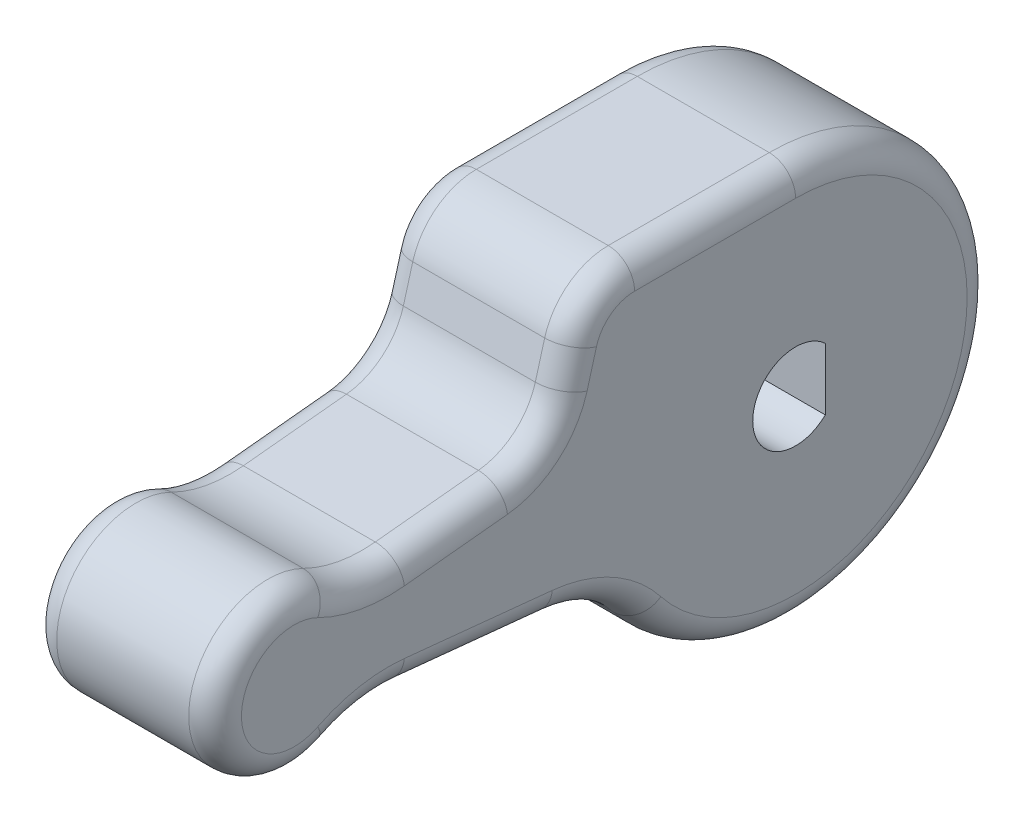
SolidWorks part; units mm, degrees
material "ABS"
ref_plane "Front Plane" through (0, 0, 0) normal (0, 0, 1) x (1, 0, 0)
ref_plane "Top Plane" through (0, 0, 0) normal (0, 1, 0) x (1, 0, 0)
ref_plane "Right Plane" through (0, 0, 0) normal (1, 0, 0) x (0, 0, -1)
sketch "Sketch1" plane through (0, 0, 0) normal (1, 0, 0) x (0, 0, -1)
  line L0 (1.125, -1.1726) -> (1.125, 1.1726)
  line L1 (-22, 0) -> (-19, 0) construction
  line L2 (-19, 0) -> (0, 0) construction
  line L3 (-16.7639, 2) -> (-6.8739, 3)
  line L4 (-16.7639, -2) -> (-6.8739, -3)
  line L5 (0, 0) -> (7.5, 0) construction
  line L6 (-1.625, 0) -> (1.125, 0) construction
  arc A0 (1.125, 1.1726) -> (1.125, -1.1726) centre (0, 0) ccw
  arc A1 (-6.8739, -3) -> (-6.8739, 3) centre (0, 0) ccw
  arc A2 (-16.7639, 2) -> (-16.7639, -2) centre (-19, 0) ccw
  dimension "D1" = 6
  dimension "D2" = 15
  dimension "D4" = 6
  dimension "D6" = 1.625
  dimension "D3" = 22
  dimension "D5" = 4
  dimension "D7" = 2.75
extrude "Boss-Extrude1" add sketch "Sketch1" along normal mid plane 7
fillet "Fillet1" radius 5 4 edges at (0, 2, 16.7639) (0, -3, 6.8739) (0, -2, 16.7639) (0, 3, 6.8739)
ref_plane "Plane1" through (0, 0, -7.625) normal (0, 0, 1) x (1, 0, 0)
hole_wizard "Hole1" positions "Sketch2" profile "Sketch3" legacy
sketch "Sketch2" plane through (0, 0, -7.625) normal (0, 0, 1) x (1, 0, 0)
  point P0 (0, 0)
sketch "Sketch3" plane through (0, 0, -7.625) normal (1, 0, 0) x (0, 1, 0)
  line L0 (0, 0) -> (0, 8)
  line L1 (0, 8) -> (1.25, 8)
  line L2 (1.25, 8) -> (1.25, 3)
  line L3 (1.25, 3) -> (1.75, 3)
  line L4 (1.75, 3) -> (1.75, 0)
  line L5 (1.75, 0) -> (0, 0)
  line L6 (0, 110) -> (0, -10) construction
  dimension "Diameter" = 2.5
  dimension "Depth" = 8
  dimension "C-Bore Diameter" = 3.5
  dimension "C-Bore Depth" = 3
sketch "Sketch4" plane through (3.5, 0, 0) normal (1, 0, 0) x (0, 0, -1)
  line L0 (0, 7.5) -> (-8, 7.5)
  line L1 (-8, 7.5) -> (-9.3226, 2.7524)
  arc A0 (-5.8954, -4.6362) -> (-5.8954, 4.6362) centre (0, 0) ccw construction
  arc A1 (-9.3226, 2.7524) -> (-5.8954, 4.6362) centre (-9.8256, 7.727) ccw construction
  arc A2 (-9.3226, 2.7524) -> (-5.8954, 4.6362) centre (-9.8256, 7.727) ccw
  arc A3 (0, 7.5) -> (-5.8954, 4.6362) centre (0, 0) ccw
  dimension "D1" = 8
extrude "Boss-Extrude2" add sketch "Sketch4" against normal through all
fillet "Fillet3" radius 2.5 2 edges at (0, 2.7524, 9.3226) (0, 7.5, 8)
fillet "Fillet2" radius 1 22 edges at (-3.5, -3.3453, 7.4172) (-3.5, -2.469, 12.1257) (-3.5, -2.2417, 16.3308) (-3.5, 0, 22) (-3.5, 2.2417, 16.3308) (-3.5, 2.3831, 12.975) (3.5, -3.3453, 7.4172) (3.5, -2.469, 12.1257) (3.5, -2.2417, 16.3308) (3.5, 0, 22) (3.5, 2.2417, 16.3308) (3.5, 2.3831, 12.975) (-3.5, -3.2771, -6.7462) (3.5, -3.2771, -6.7462) (-3.5, 7.5, 3.0506) (3.5, 7.5, 3.0506) (-3.5, 3.1558, 9.6623) (-3.5, 5.034, 8.687) (3.5, 5.034, 8.687) (-3.5, 6.9909, 7.6133) (3.5, 3.1558, 9.6623) (3.5, 6.9909, 7.6133)
